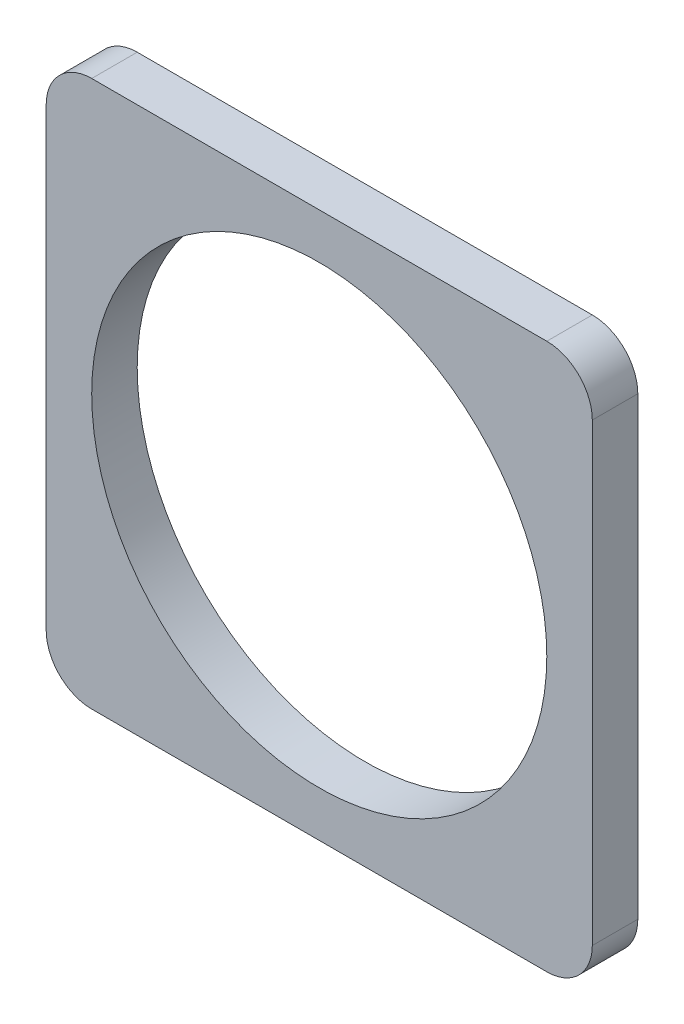
SolidWorks part; units mm, degrees
ref_plane "Front Plane" through (0, 0, 0) normal (0, 0, 1) x (1, 0, 0)
ref_plane "Top Plane" through (0, 0, 0) normal (0, 1, 0) x (1, 0, 0)
ref_plane "Right Plane" through (0, 0, 0) normal (1, 0, 0) x (0, 0, -1)
sketch "Sketch1" plane through (0, 0, 0) normal (0, 0, 1) x (1, 0, 0)
  line L1 (-50, 60) -> (50, 60)
  line L2 (-60, 50) -> (-60, -50)
  line L3 (-50, -60) -> (50, -60)
  line L4 (60, 50) -> (60, -50)
  line L5 (-60, 60) -> (60, -60) construction
  line L6 (-60, -60) -> (60, 60) construction
  arc A0 (-60, -50) -> (-50, -60) centre (-50, -50) ccw
  arc A1 (50, -60) -> (60, -50) centre (50, -50) ccw
  arc A2 (50, 60) -> (60, 50) centre (50, 50) cw
  arc A3 (-50, 60) -> (-60, 50) centre (-50, 50) ccw
  point P0 (0, 0)
  dimension "D3" = 10
  dimension "D1" = 120
  dimension "D2" = 120
extrude "Boss-Extrude1" add sketch "Sketch1" along normal blind 10 contours A3 L2 A0 L3 A1 L4 A2 L1
sketch "Sketch2" plane through (0, 0, 10) normal (0, 0, 1) x (1, 0, 0)
  line L0 (0, 0) -> (0, 40) construction
  line L1 (-50, 50) -> (50, 50) construction
  line L2 (-50, 50) -> (-50, -50) construction
  line L3 (-50, -50) -> (50, -50) construction
  line L4 (50, 50) -> (50, -50) construction
  line L5 (-50, 50) -> (50, -50) construction
  line L6 (-50, -50) -> (50, 50) construction
  line L7 (0, 40) -> (-40, 40) construction
  line L8 (-40, 40) -> (-40, 0) construction
  line L9 (-40, 0) -> (0, 0) construction
  line L11 (0, 20) -> (-20, 20) construction
  line L12 (-20, 40) -> (-20, 20) construction
  circle A0 centre (0, 40) radius 4 construction
  circle A1 centre (0, 20) radius 4 construction
  circle A2 centre (0, 0) radius 4 construction
  circle A3 centre (-20, 20) radius 4 construction
  circle A4 centre (-20, 40) radius 4 construction
  circle A5 centre (-40, 40) radius 4 construction
  circle A6 centre (0, 0) radius 4 construction
  circle A7 centre (20, 0) radius 4 construction
  circle A8 centre (40, 0) radius 4 construction
  circle A9 centre (40, 20) radius 4 construction
  circle A10 centre (40, 40) radius 4 construction
  circle A11 centre (20, 20) radius 4 construction
  circle A12 centre (0, 0) radius 4 construction
  circle A13 centre (0, -20) radius 4 construction
  circle A14 centre (0, -40) radius 4 construction
  circle A15 centre (20, -40) radius 4 construction
  circle A16 centre (40, -40) radius 4 construction
  circle A17 centre (20, -20) radius 4 construction
  circle A18 centre (0, 0) radius 4
  circle A19 centre (-20, 0) radius 4 construction
  circle A20 centre (-40, 0) radius 4 construction
  circle A21 centre (-40, -20) radius 4 construction
  circle A22 centre (-40, -40) radius 4 construction
  circle A23 centre (-20, -20) radius 4 construction
  point P0 (0, 0)
  point P55 (0, 0)
  dimension "D4" = 8
  dimension "D1" = 100
  dimension "D2" = 100
  dimension "D3" = 40
  dimension "D5" = 4
sketch "Sketch3" plane through (0, 0, 10) normal (0, 0, 1) x (1, 0, 0)
  circle A0 centre (0, 0) radius 50
  dimension "D1" = 100
extrude "Cut-Extrude2" cut sketch "Sketch3" against normal blind 10
